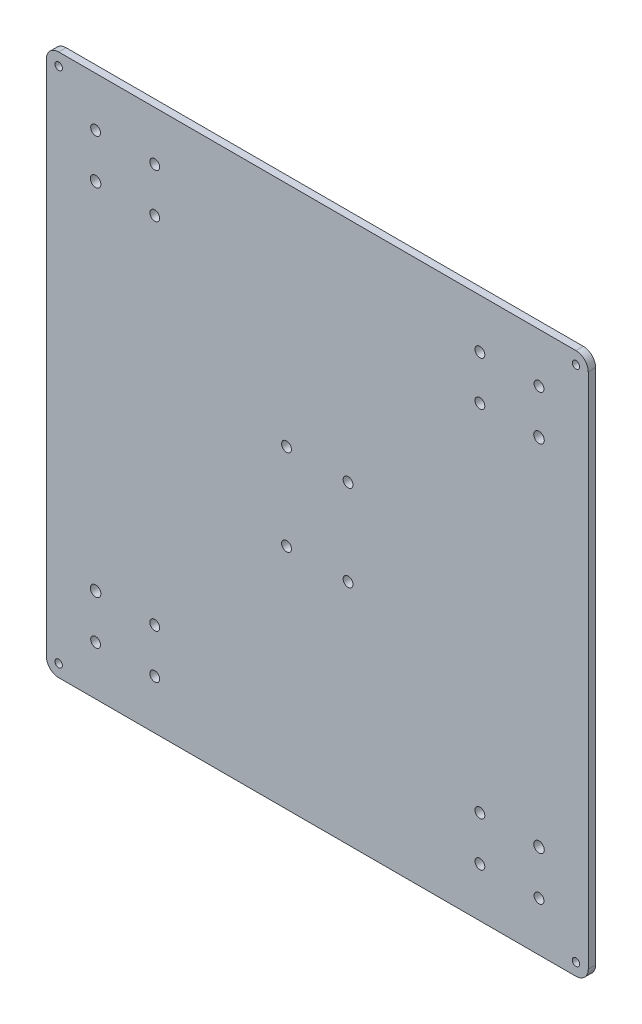
SolidWorks part; units mm, degrees
ref_plane "Płaszczyzna przednia" through (0, 0, 0) normal (0, 0, 1) x (1, 0, 0)
ref_plane "Płaszczyzna górna" through (0, 0, 0) normal (0, 1, 0) x (1, 0, 0)
ref_plane "Płaszczyzna prawa" through (0, 0, 0) normal (1, 0, 0) x (0, 0, -1)
sketch "Szkic1" plane through (0, 0, 0) normal (0, 0, 1) x (1, 0, 0)
  line L1 (-110, -110) -> (110, -110)
  line L2 (-110, -110) -> (-110, 110)
  line L3 (-110, 110) -> (110, 110)
  line L4 (110, -110) -> (110, 110)
  line L5 (-110, -110) -> (110, 110) construction
  line L6 (-110, 110) -> (110, -110) construction
  point P0 (0, 0)
  dimension "D1" = 220
  dimension "D2" = 220
extrude "Dodanie-wyciągnięcie1" add sketch "Szkic1" along normal blind 3
sketch "Szkic2" plane through (0, 0, 3) normal (0, 0, 1) x (1, 0, 0)
  circle A0 centre (105, 105) radius 1.5
extrude "Wytnij-wyciągnięcie1" cut sketch "Szkic2" against normal blind 3
sketch "Szkic3" plane through (0, 0, 3) normal (0, 0, 1) x (1, 0, 0)
  circle A0 centre (-105, 105) radius 1.5
  circle A1 centre (-105, -105) radius 1.5
  circle A2 centre (105, -105) radius 1.5
  dimension "D1" = 3
  dimension "D2" = 3
  dimension "D3" = 3
extrude "Wytnij-wyciągnięcie2" cut sketch "Szkic3" against normal blind 3
sketch "Szkic4" plane through (0, 0, 3) normal (0, 0, 1) x (1, 0, 0)
  circle A0 centre (-12.5, -17.5) radius 2
  circle A1 centre (-12.5, 17.5) radius 2
  circle A2 centre (12.5, 17.5) radius 2
  circle A3 centre (12.5, -17.5) radius 2
  point P1 (0, 0)
  dimension "D3" = 4
  dimension "D4" = 4
  dimension "D5" = 4
  dimension "D6" = 4
extrude "Wytnij-wyciągnięcie3" cut sketch "Szkic4" against normal blind 3
fillet "Zaokrąglenie1" radius 5 4 edges at (110, 110, 1.5) (-110, 110, 1.5) (-110, -110, 1.5) (110, -110, 1.5)
sketch "Szkic6" plane through (0, 0, 0) normal (0, 0, -1) x (-1, 0, 0)
  circle A0 centre (-90, -72) radius 2.1402
  circle A1 centre (-66, -72) radius 2
  circle A2 centre (-66, -90) radius 2
  circle A3 centre (-90, -90) radius 2
  dimension "D3" = 24
  dimension "D4" = 18
extrude "Wytnij-wyciągnięcie4" cut sketch "Szkic6" against normal up to next
mirror "Lustro1" about plane through (0, 0, 0) normal (1, 0, 0) of "Wytnij-wyciągnięcie4"
mirror "Lustro2" about plane through (0, 0, 0) normal (0, 1, 0) of "Lustro1", "Wytnij-wyciągnięcie4"
